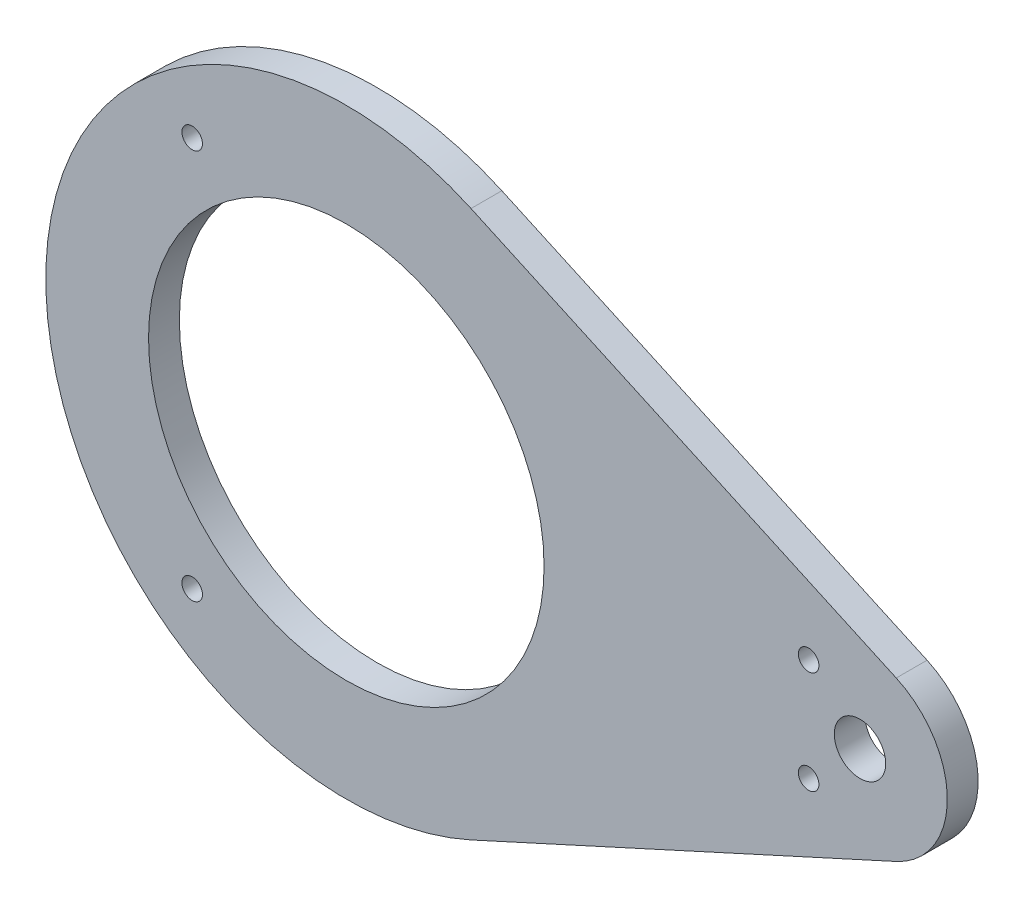
SolidWorks part; units mm, degrees
ref_plane "Face" through (0, 0, 0) normal (0, 0, 1) x (1, 0, 0)
ref_plane "Dessus" through (0, 0, 0) normal (0, 1, 0) x (1, 0, 0)
ref_plane "Droite" through (0, 0, 0) normal (1, 0, 0) x (0, 0, -1)
sketch "Esquisse1" plane through (0, 0, 0) normal (0, 0, 1) x (1, 0, 0)
  line L0 (50, 0) -> (0, 0) construction
  line L1 (12.1387, 26.6123) -> (53.5275, 7.7335)
  line L2 (-29.25, 0) -> (0, 0) construction
  line L3 (12.1388, -26.6123) -> (53.5275, -7.7335)
  line L4 (58.5, 0) -> (50, 0) construction
  circle A0 centre (0, 0) radius 19.25
  circle A1 centre (50, 0) radius 2.5
  arc A2 (12.1387, 26.6123) -> (12.1388, -26.6123) centre (0, 0) ccw
  arc A3 (53.5275, 7.7335) -> (53.5275, -7.7335) centre (50, 0) cw
  dimension "D1" = 38.5
  dimension "D2" = 5
  dimension "D4" = 10
  dimension "D5" = 6
  dimension "D3" = 50
extrude "Boss.-Extru.1" add sketch "Esquisse1" along normal blind 42
sketch "Esquisse2" plane through (5.2188, 0, 0) normal (0, 1, 0) x (1, 0, 0)
  line L0 (33.3087, -36) -> (-56.6913, -36)
  line L1 (-56.6913, -36) -> (-56.6913, -6)
  line L2 (48.3087, -21) -> (6.9199, -21) construction
  line L3 (48.3087, -42) -> (48.3087, 0) construction
  line L4 (6.9199, -42) -> (6.9199, 0) construction
  line L5 (48.3087, -42) -> (6.9199, -42) construction
  line L6 (33.3087, -36) -> (33.3087, -6)
  line L7 (33.3087, -6) -> (-56.6913, -6)
  point P13 (33.3087, -21)
  point P14 (-56.6913, -21)
  dimension "D1" = 6
  dimension "D2" = 90
  dimension "D3" = 15
extrude "Enlèv. mat.-Extru.1" cut sketch "Esquisse2" against normal through all both and the other way through all
sketch "Esquisse3" plane through (0, 0, 42) normal (0, 0, 1) x (1, 0, 0)
  line L0 (50, 0) -> (45, 0) construction
  line L1 (45, 0) -> (45, 5) construction
  line L2 (-15, 19) -> (-15, 0) construction
  line L3 (-15, 0) -> (50, 0) construction
  circle A0 centre (45, 5) radius 1
  circle A1 centre (45, -5) radius 1
  circle A2 centre (-15, 19) radius 1
  circle A3 centre (-15, -19) radius 1
  dimension "D1" = 2
  dimension "D2" = 5
  dimension "D3" = 5
  dimension "D4" = 65
  dimension "D5" = 19
extrude "Enlèv. mat.-Extru.2" cut sketch "Esquisse3" against normal up to vertex (42 mm away) up to point (53.5275, 7.7335, 0)
sketch "Esquisse4" plane through (0, 0, 0) normal (0, 1, 0) x (1, 0, 0)
  line L0 (58.5, -42) -> (58.5, 0) construction
  line L1 (-29.25, -42) -> (58.5, -42)
  line L2 (-29.25, -42) -> (-29.25, -3)
  line L3 (-29.25, -3) -> (58.5, -3)
  line L4 (58.5, -42) -> (58.5, -3)
  line L5 (53.5275, 0) -> (12.1388, 0) construction
  dimension "D1" = 3
extrude "Enlèv. mat.-Extru.3" cut sketch "Esquisse4" against normal through all both and the other way through all
